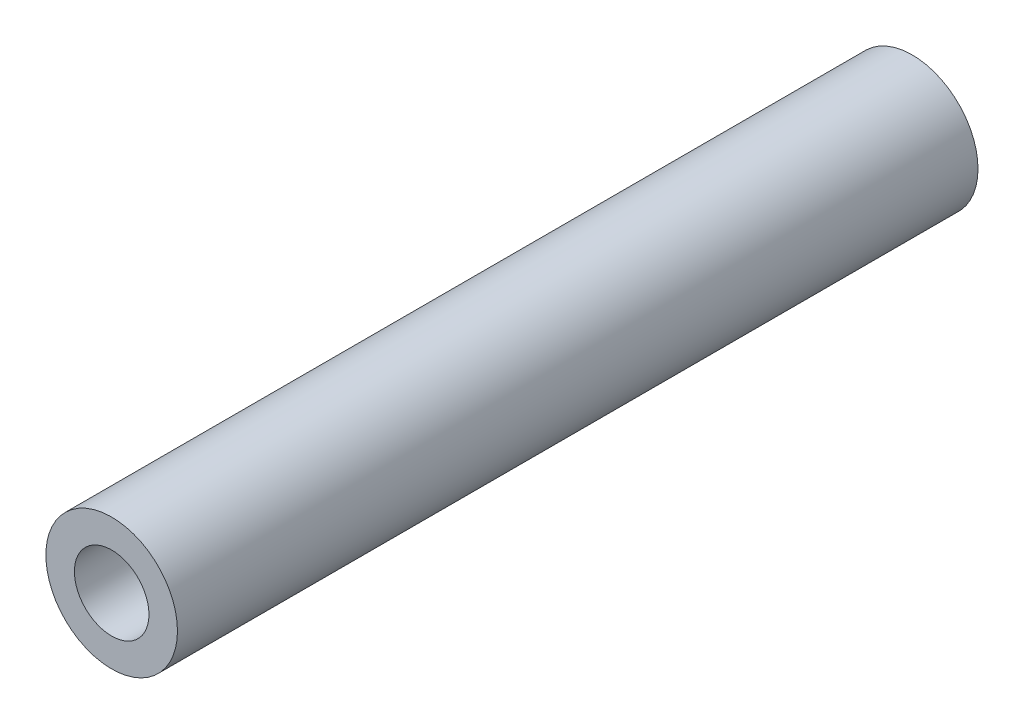
SolidWorks part; units mm, degrees
ref_plane "Front Plane" through (0, 0, 0) normal (0, 0, 1) x (1, 0, 0)
ref_plane "Top Plane" through (0, 0, 0) normal (0, 1, 0) x (1, 0, 0)
ref_plane "Right Plane" through (0, 0, 0) normal (1, 0, 0) x (0, 0, -1)
sketch "Sketch1" plane through (0, 0, 0) normal (0, 0, 1) x (1, 0, 0)
  circle A0 centre (0, 0) radius 3
  circle A1 centre (0, 0) radius 1.7
extrude "Ring_Envelope" add sketch "Sketch1" along normal blind 36.5
